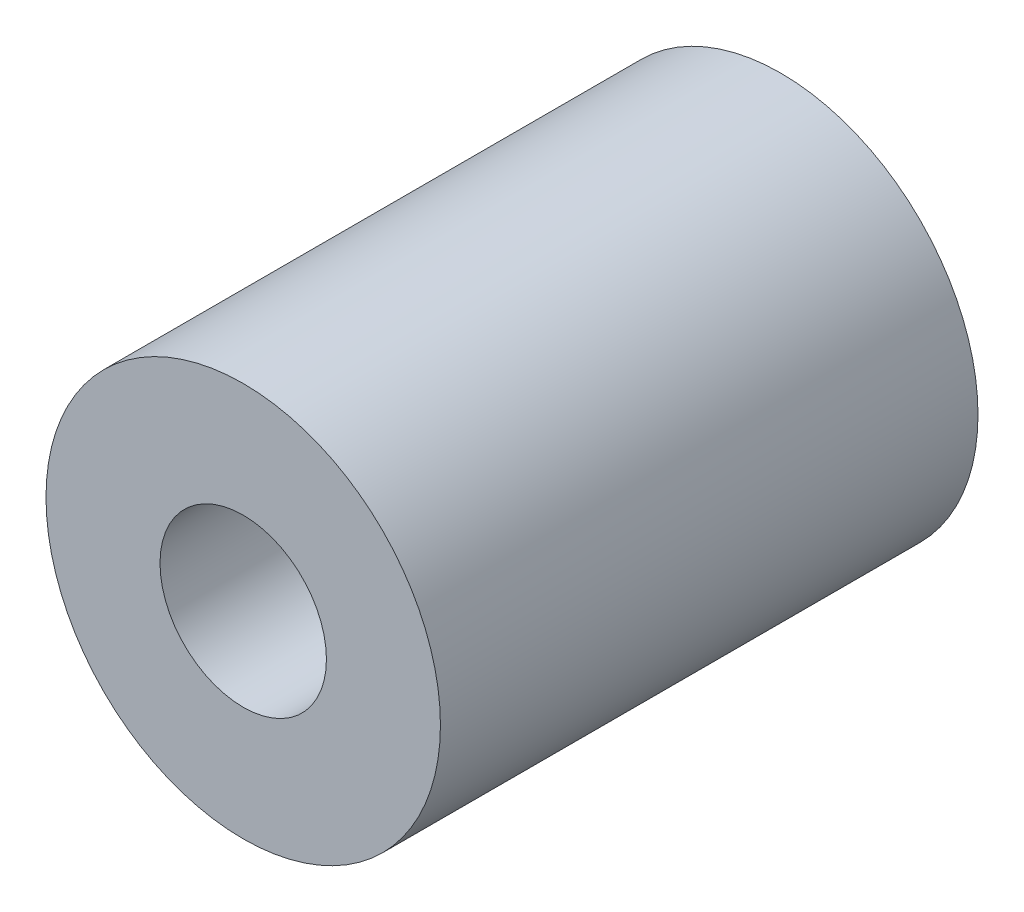
SolidWorks part; units mm, degrees
ref_plane "Plano frontal" through (0, 0, 0) normal (0, 0, 1) x (1, 0, 0)
ref_plane "Plano superior" through (0, 0, 0) normal (0, 1, 0) x (1, 0, 0)
ref_plane "Plano direito" through (0, 0, 0) normal (1, 0, 0) x (0, 0, -1)
sketch "Esboço1" plane through (0, 0, 0) normal (0, 0, 1) x (1, 0, 0)
  circle A0 centre (0, 0) radius 2.5
  circle A1 centre (0, 0) radius 5.925
  dimension "D1" = 5
  dimension "D2" = 11.85
extrude "Ressalto-extrusão1" add sketch "Esboço1" along normal blind 16.15
